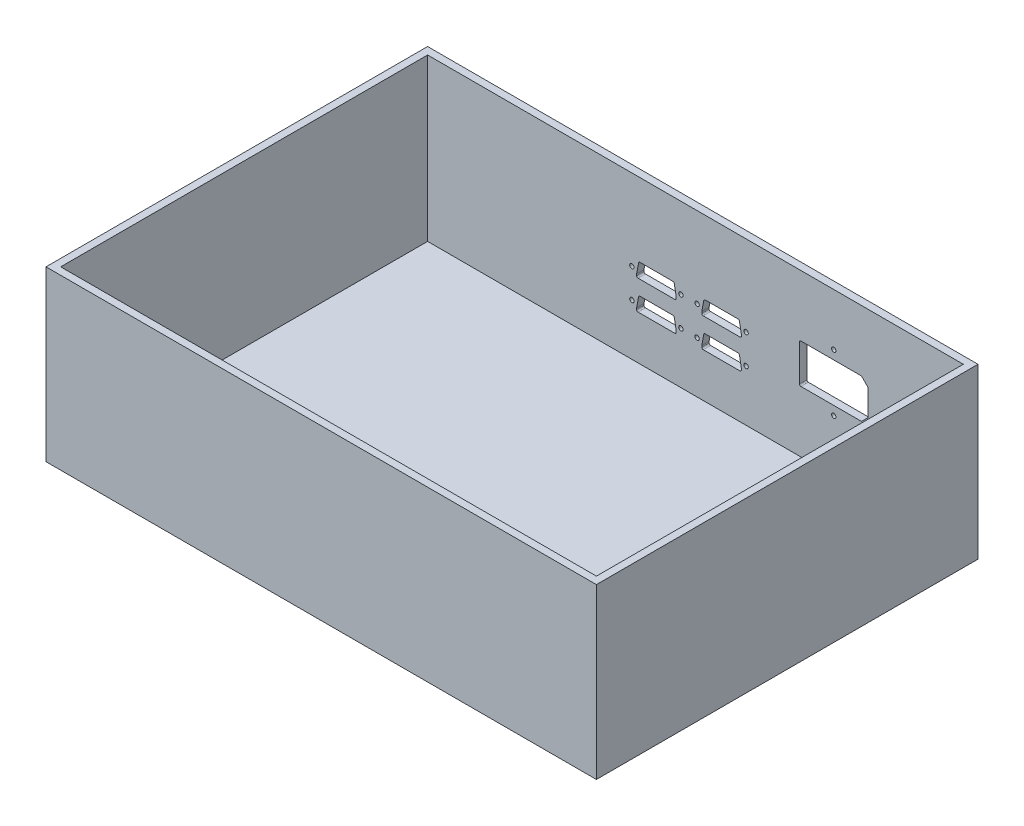
SolidWorks part; units mm, degrees
ref_plane "Спереди" through (0, 0, 0) normal (0, 0, 1) x (1, 0, 0)
ref_plane "Сверху" through (0, 0, 0) normal (0, 1, 0) x (1, 0, 0)
ref_plane "Справа" through (0, 0, 0) normal (1, 0, 0) x (0, 0, -1)
other "Configuration Table"
sketch "Эскиз1" plane through (0, 0, 0) normal (0, 1, 0) x (1, 0, 0)
  line L1 (-187.5, -130) -> (187.5, -130)
  line L2 (-187.5, -130) -> (-187.5, 130)
  line L3 (-187.5, 130) -> (187.5, 130)
  line L4 (187.5, -130) -> (187.5, 130)
  line L5 (-187.5, -130) -> (187.5, 130) construction
  line L6 (-187.5, 130) -> (187.5, -130) construction
  point P0 (0, 0)
  dimension "D1" = 375
  dimension "D2" = 260
extrude "Бобышка-Вытянуть1" add sketch "Эскиз1" along normal blind 115
shell "Оболочка1" thickness 5
sketch "Эскиз2" plane through (0, 0, -130) normal (0, 0, -1) x (-1, 0, 0)
  line L0 (-187.5, 60) -> (187.5, 60) construction
  line L3 (-187.5, 115) -> (-187.5, 0) construction
  line L4 (187.5, 115) -> (187.5, 0) construction
  line L5 (-187.5, 40) -> (187.5, 40) construction
  line L6 (-187.5, 20) -> (187.5, 20) construction
  line L7 (-187.5, 0) -> (187.5, 0) construction
  line L9 (-137.5, 0) -> (-137.5, 115) construction
  line L10 (-187.5, 115) -> (187.5, 115) construction
  line L32 (187.5, 80) -> (-187.5, 80) construction
  line L33 (187.5, 100) -> (-187.5, 100) construction
  point P16 (26.6, 60)
  point P17 (39.8853, 80.5543)
  point P18 (41.3853, 72.5543)
  point P19 (-17.8, 60)
  point P20 (15.8853, 80.5543)
  point P21 (-94.2, 60)
  point P22 (-96.4863, 60)
  point P26 (26.6, 40)
  point P27 (-5.8, 65)
  point P28 (40.0945, 60.145)
  point P29 (41.5945, 52.145)
  point P30 (-4.3, 57)
  point P31 (-17.8, 40)
  point P32 (16.0945, 60.145)
  point P33 (-5.5908, 64.5907)
  point P34 (-4.0908, 56.5907)
  point P35 (-29.5908, 64.5907)
  point P39 (-29.8, 65)
  point P55 (0, 0)
  point P56 (-94.2, 60)
  point P57 (0, 0)
  line B0 (-31.3, 57) -> (-29.9529, 64.1843)
  line B1 (-4.3171, 57.0913) -> (-5.6471, 64.1843)
  line B2 (-37.5, 53.4) -> (1.9, 53.4) construction
  line B3 (-37.5, 53.4) -> (-37.5, 66.6) construction
  line B4 (-37.5, 66.6) -> (1.9, 66.6) construction
  line B5 (1.9, 53.4) -> (1.9, 66.6) construction
  line B6 (-30.3, 55) -> (-5.3, 55)
  line B7 (-31.3, 56) -> (-31.3, 57)
  line B8 (-28.9701, 65) -> (-6.6299, 65)
  line B9 (-4.3, 56) -> (-4.3, 56.9071)
  line B10 (-31.3, 55) -> (-4.3, 65) construction
  line B11 (-31.3, 65) -> (-4.3, 55) construction
  line B12 (-17.8, 53.4) -> (-17.8, 66.6) construction
  arc B13 (-5.6471, 64.1843) -> (-6.6299, 65) centre (-6.6299, 64) ccw
  arc B14 (-4.3, 56.9071) -> (-4.3171, 57.0913) centre (-5.3, 56.9071) ccw
  arc B15 (-5.3, 55) -> (-4.3, 56) centre (-5.3, 56) ccw
  arc B16 (-30.3, 55) -> (-31.3, 56) centre (-30.3, 56) cw
  arc B17 (-29.9529, 64.1843) -> (-28.9701, 65) centre (-28.9701, 64) cw
  circle B18 centre (-34.5, 60) radius 1.5
  circle B19 centre (-1.1, 60) radius 1.5
  line B20 (13.1, 57) -> (14.4471, 64.1843)
  line B21 (40.0829, 57.0913) -> (38.7529, 64.1843)
  line B22 (6.9, 53.4) -> (6.9, 66.6) construction
  line B23 (14.1, 55) -> (39.1, 55)
  line B24 (13.1, 56) -> (13.1, 57)
  line B25 (15.4299, 65) -> (37.7701, 65)
  line B26 (40.1, 56) -> (40.1, 56.9071)
  arc B27 (38.7529, 64.1843) -> (37.7701, 65) centre (37.7701, 64) ccw
  arc B28 (40.1, 56.9071) -> (40.0829, 57.0913) centre (39.1, 56.9071) ccw
  arc B29 (39.1, 55) -> (40.1, 56) centre (39.1, 56) ccw
  arc B30 (14.1, 55) -> (13.1, 56) centre (14.1, 56) cw
  arc B31 (14.4471, 64.1843) -> (15.4299, 65) centre (15.4299, 64) cw
  circle B32 centre (9.9, 60) radius 1.5
  circle B33 centre (43.3, 60) radius 1.5
  line B34 (-31.3, 37) -> (-29.9529, 44.1843)
  line B35 (-4.3171, 37.0913) -> (-5.6471, 44.1843)
  line B36 (-37.5, 33.4) -> (-37.5, 46.6) construction
  line B37 (-30.3, 35) -> (-5.3, 35)
  line B38 (-31.3, 36) -> (-31.3, 37)
  line B39 (-28.9701, 45) -> (-6.6299, 45)
  line B40 (-4.3, 36) -> (-4.3, 36.9071)
  arc B41 (-5.6471, 44.1843) -> (-6.6299, 45) centre (-6.6299, 44) ccw
  arc B42 (-4.3, 36.9071) -> (-4.3171, 37.0913) centre (-5.3, 36.9071) ccw
  arc B43 (-5.3, 35) -> (-4.3, 36) centre (-5.3, 36) ccw
  arc B44 (-30.3, 35) -> (-31.3, 36) centre (-30.3, 36) cw
  arc B45 (-29.9529, 44.1843) -> (-28.9701, 45) centre (-28.9701, 44) cw
  circle B46 centre (-34.5, 40) radius 1.5
  circle B47 centre (-1.1, 40) radius 1.5
  line B48 (13.1, 37) -> (14.4471, 44.1843)
  line B49 (40.0829, 37.0913) -> (38.7529, 44.1843)
  line B50 (6.9, 33.4) -> (6.9, 46.6) construction
  line B51 (14.1, 35) -> (39.1, 35)
  line B52 (13.1, 36) -> (13.1, 37)
  line B53 (15.4299, 45) -> (37.7701, 45)
  line B54 (40.1, 36) -> (40.1, 36.9071)
  arc B55 (38.7529, 44.1843) -> (37.7701, 45) centre (37.7701, 44) ccw
  arc B56 (40.1, 36.9071) -> (40.0829, 37.0913) centre (39.1, 36.9071) ccw
  arc B57 (39.1, 35) -> (40.1, 36) centre (39.1, 36) ccw
  arc B58 (14.1, 35) -> (13.1, 36) centre (14.1, 36) cw
  arc B59 (14.4471, 44.1843) -> (15.4299, 45) centre (15.4299, 44) cw
  circle B60 centre (9.9, 40) radius 1.5
  circle B61 centre (43.3, 40) radius 1.5
  line B62 (-94.2, 40.5) -> (-94.2, 79.5) construction
  line B63 (-113.1, 46.6) -> (-71.9, 46.6)
  line B64 (-117.5, 51) -> (-117.5, 69)
  line B65 (-113.1, 73.4) -> (-71.9, 73.4)
  line B66 (-70.9, 47.6) -> (-70.9, 72.4)
  line B67 (-117.5, 46.6) -> (-70.9, 73.4) construction
  line B68 (-117.5, 73.4) -> (-70.9, 46.6) construction
  line B69 (-117.5, 69) -> (-113.1, 73.4)
  line B70 (-113.1, 46.6) -> (-117.5, 51)
  circle B71 centre (-94.2, 40.5) radius 1.5
  arc B72 (-70.9, 47.6) -> (-71.9, 46.6) centre (-71.9, 47.6) cw
  arc B73 (-70.9, 72.4) -> (-71.9, 73.4) centre (-71.9, 72.4) ccw
  circle B74 centre (-94.2, 79.5) radius 1.5
  dimension "D1" = 20
  dimension "D2" = 20
  dimension "D3" = 20
  dimension "D4" = 50
  dimension "D5" = 5
  dimension "D6" = 100
  dimension "D7" = 8
  dimension "D8" = 24
  dimension "D9" = 20
  dimension "D11" = 24
  dimension "D12" = 1.5
  dimension "D19" = 20
  dimension "D20" = 20
sketch_block_instance "Блок1-1"
sketch_block "Блок1" parameters "D6"=1, "D7"=3, "D1"=10, "D2"=27, "D3"=8, "D4"=13.2, "D5"=39.4, "D8"=3
sketch_block_instance "Блок1-4"
sketch_block_instance "Блок1-5"
sketch_block_instance "Блок1-6"
sketch_block_instance "Блок2-1"
sketch_block "Блок2" parameters "D2"=3, "D9"=1, "D1"=39, "D7"=18, "D8"=42.2
extrude "Вырез-Вытянуть1" cut sketch "Эскиз2" against normal up to surface (5 mm away) up to face at (0, 60, -125)
